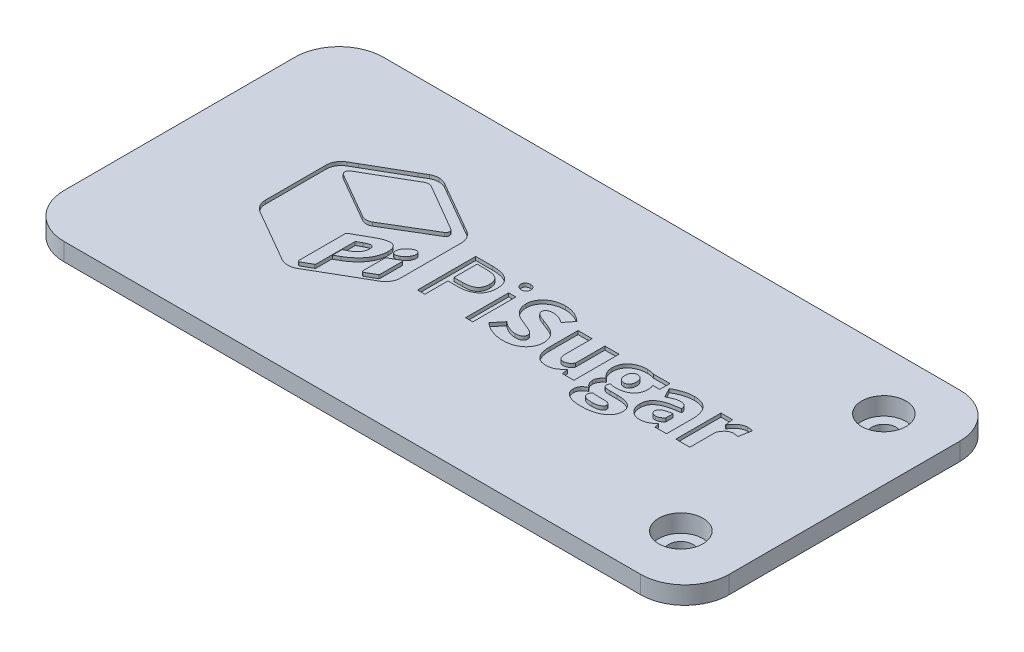
SolidWorks part; units mm, degrees
ref_plane "前视基准面" through (0, 0, 0) normal (0, 0, 1) x (1, 0, 0)
ref_plane "上视基准面" through (0, 0, 0) normal (0, 1, 0) x (1, 0, 0)
ref_plane "右视基准面" through (0, 0, 0) normal (1, 0, 0) x (0, 0, -1)
sketch "zero" plane through (0, 0, 0) normal (0, 1, 0) x (1, 0, 0)
  line L1 (-29.5, 15) -> (29.5, 15)
  line L2 (-32.5, 12) -> (-32.5, -12)
  line L3 (-29.5, -15) -> (29.5, -15)
  line L4 (32.5, 12) -> (32.5, -12)
  line L5 (-32.5, 15) -> (32.5, -15) construction
  line L6 (-32.5, -15) -> (32.5, 15) construction
  line L7 (-25.7, -15) -> (-14.5, -15)
  line L8 (-25.7, -15) -> (-25.7, -9.6569)
  line L9 (-25.7, -9.6569) -> (-14.5, -9.6569)
  line L10 (-14.5, -15) -> (-14.5, -9.6569)
  line L11 (5.2, -15) -> (12.7, -15)
  line L12 (5.2, -15) -> (5.2, -11)
  line L13 (5.2, -11) -> (12.7, -11)
  line L14 (12.7, -15) -> (12.7, -11)
  line L15 (17.8, -15) -> (25.3, -15)
  line L16 (17.8, -15) -> (17.8, -11)
  line L17 (17.8, -11) -> (25.3, -11)
  line L18 (25.3, -15) -> (25.3, -11)
  line L19 (-32.5, 7.7) -> (-19.5, 7.7)
  line L20 (-32.5, 7.7) -> (-32.5, -4.3)
  line L21 (-32.5, -4.3) -> (-19.5, -4.3)
  line L22 (-19.5, 7.7) -> (-19.5, -4.3)
  line L23 (-25.5, 14) -> (25.5, 14)
  line L24 (-25.5, 14) -> (-25.5, 8.8)
  line L25 (-25.5, 8.8) -> (25.5, 8.8)
  line L26 (25.5, 14) -> (25.5, 8.8)
  line L27 (-19.5, 7.2329) -> (-35.5, 7.2329)
  line L28 (-19.5, 7.2329) -> (-19.5, -3.7671)
  line L29 (-19.5, -3.7671) -> (-35.5, -3.7671)
  line L30 (-35.5, 7.2329) -> (-35.5, -3.7671)
  arc A0 (29.5, -15) -> (32.5, -12) centre (29.5, -12) ccw
  arc A1 (29.5, 15) -> (32.5, 12) centre (29.5, 12) cw
  arc A2 (-32.5, -12) -> (-29.5, -15) centre (-29.5, -12) ccw
  arc A3 (-29.5, 15) -> (-32.5, 12) centre (-29.5, 12) ccw
  circle A4 centre (-29, 11.4) radius 3
  circle A5 centre (-29, -11.5) radius 3
  circle A6 centre (29, 11.4) radius 3
  circle A7 centre (29, -11.5) radius 3
  circle A8 centre (-29, 11.4) radius 1.375
  circle A9 centre (-29, -11.5) radius 1.375
  circle A10 centre (29, -11.5) radius 1.375
  circle A11 centre (29, 11.4) radius 1.375
  point P0 (0, 0)
  dimension "D3" = 3
  dimension "D4" = 6
  dimension "D9" = 2.75
  dimension "D1" = 65
  dimension "D2" = 30
  dimension "D5" = 3.6
  dimension "D6" = 3.5
  dimension "D7" = 3.5
  dimension "D8" = 3.5
  dimension "D10" = 12
  dimension "D11" = 7.3
  dimension "D12" = 13
  dimension "D13" = 11.2
  dimension "D14" = 6.8
  dimension "D15" = 19.7
  dimension "D16" = 7.5
  dimension "D17" = 7.5
  dimension "D18" = 5.1
  dimension "D19" = 4
  dimension "D20" = 5.2
  dimension "D21" = 7
  dimension "D22" = 7
  dimension "D23" = 1
  dimension "D24" = 11
  dimension "D25" = 16
sketch "sugar" plane through (0, 0, 0) normal (0, 1, 0) x (1, 0, 0)
  line L1 (-29.5, 15) -> (29.5, 15)
  line L2 (-32.5, 12) -> (-32.5, -12)
  line L3 (-29.5, -15) -> (29.5, -15)
  line L4 (32.5, 12) -> (32.5, -12)
  line L5 (-32.5, 15) -> (32.5, -15) construction
  line L6 (-32.5, -15) -> (32.5, 15) construction
  line L7 (23.5, -11.5) -> (19.5, -11.5)
  line L8 (23.5, -11.5) -> (23.5, -13.9082)
  line L9 (23.5, -13.9082) -> (19.5, -13.9082)
  line L10 (19.5, -11.5) -> (19.5, -13.9082)
  line L11 (16, -11.0071) -> (8.5, -11.0071)
  line L12 (16, -11.0071) -> (16, -15)
  line L13 (16, -15) -> (8.5, -15)
  line L14 (8.5, -11.0071) -> (8.5, -15)
  line L15 (20.5, -13.9082) -> (22.5, -13.9082)
  line L16 (20.5, -13.9082) -> (20.5, -14.8173)
  line L17 (20.5, -14.8173) -> (22.5, -14.8173)
  line L18 (22.5, -13.9082) -> (22.5, -14.8173)
  arc A0 (29.5, 15) -> (32.5, 12) centre (29.5, 12) cw
  arc A1 (29.5, -15) -> (32.5, -12) centre (29.5, -12) ccw
  arc A2 (-32.5, -12) -> (-29.5, -15) centre (-29.5, -12) ccw
  arc A3 (-29.5, 15) -> (-32.5, 12) centre (-29.5, 12) ccw
  circle A4 centre (-29, 11.4) radius 3
  circle A5 centre (-29, 11.4) radius 1.375
  circle A6 centre (-29, -11.5) radius 3
  circle A7 centre (-29, -11.5) radius 1.375
  circle A8 centre (29, 11.4) radius 3
  circle A9 centre (29, 11.4) radius 1.375
  circle A10 centre (29, -11.5) radius 3
  circle A11 centre (29, -11.5) radius 1.375
  dimension "D3" = 3
  dimension "D1" = 65
  dimension "D2" = 30
  dimension "D4" = 9
  dimension "D5" = 4
  dimension "D6" = 3.5
  dimension "D7" = 7.5
  dimension "D8" = 2
  dimension "D9" = 1
sketch "case" plane through (0, 0, 0) normal (0, 1, 0) x (1, 0, 0)
  line L1 (-34.0422, 18) -> (30.9578, 18)
  line L2 (-39.0422, 13) -> (-39.0422, -13)
  line L3 (-34.0422, -18) -> (30.9578, -18)
  line L4 (35.9578, 13) -> (35.9578, -13)
  line L5 (-39.0422, 18) -> (35.9578, -18) construction
  line L6 (-39.0422, -18) -> (35.9578, 18) construction
  arc A0 (-39.0422, -13) -> (-34.0422, -18) centre (-34.0422, -13) ccw
  arc A1 (30.9578, -18) -> (35.9578, -13) centre (30.9578, -13) ccw
  arc A2 (30.9578, 18) -> (35.9578, 13) centre (30.9578, 13) cw
  arc A3 (-34.0422, 18) -> (-39.0422, 13) centre (-34.0422, 13) ccw
  point P0 (-1.5422, 0)
  point P3 (-1.5422, 0)
  dimension "D3" = 5
  dimension "D1" = 75
  dimension "D2" = 36
extrude "凸台-拉伸2" add sketch "case" along normal blind 2
sketch "草图2" plane through (0, 0, 0) normal (0, 1, 0) x (1, 0, 0)
  line L4 (-34.0422, -14.7) -> (30.9578, -14.7)
  line L5 (32.6578, -13) -> (32.6578, 13)
  line L6 (30.9578, 14.7) -> (-34.0422, 14.7)
  line L7 (-35.7422, 13) -> (-35.7422, -13)
  line L8 (33.8578, -13) -> (33.8578, 13)
  line L9 (30.9578, 15.9) -> (-34.0422, 15.9)
  line L10 (-36.9422, 13) -> (-36.9422, -13)
  line L11 (-34.0422, -15.9) -> (30.9578, -15.9)
  line L12 (33.8578, -13) -> (33.8578, 13)
  line L13 (30.9578, 15.9) -> (-34.0422, 15.9)
  line L14 (-36.9422, 13) -> (-36.9422, -13)
  line L15 (-34.0422, -15.9) -> (30.9578, -15.9)
  arc A4 (30.9578, -14.7) -> (32.6578, -13) centre (30.9578, -13) ccw
  arc A5 (32.6578, 13) -> (30.9578, 14.7) centre (30.9578, 13) ccw
  arc A6 (-34.0422, 14.7) -> (-35.7422, 13) centre (-34.0422, 13) ccw
  arc A7 (-35.7422, -13) -> (-34.0422, -14.7) centre (-34.0422, -13) ccw
  arc A8 (30.9578, -15.9) -> (33.8578, -13) centre (30.9578, -13) ccw
  arc A9 (33.8578, 13) -> (30.9578, 15.9) centre (30.9578, 13) ccw
  arc A10 (-34.0422, 15.9) -> (-36.9422, 13) centre (-34.0422, 13) ccw
  arc A11 (-36.9422, -13) -> (-34.0422, -15.9) centre (-34.0422, -13) ccw
  arc A12 (30.9578, -15.9) -> (33.8578, -13) centre (30.9578, -13) ccw
  arc A13 (33.8578, 13) -> (30.9578, 15.9) centre (30.9578, 13) ccw
  arc A14 (-34.0422, 15.9) -> (-36.9422, 13) centre (-34.0422, 13) ccw
  arc A15 (-36.9422, -13) -> (-34.0422, -15.9) centre (-34.0422, -13) ccw
  dimension "D1" = 2.1
  dimension "D2" = 1.2
extrude "凸台-拉伸3" add sketch "草图2" against normal blind 1
sketch "草图4" plane through (0, 0, 0) normal (0, 1, 0) x (1, 0, 0)
  line L1 (-35.7422, -5) -> (-31.7422, -5)
  line L2 (-35.7422, -5) -> (-35.7422, 5)
  line L3 (-35.7422, 5) -> (-31.7422, 5)
  line L4 (-31.7422, -5) -> (-31.7422, 5)
  line L5 (-35.7422, -5) -> (-31.7422, 5) construction
  line L6 (-35.7422, 5) -> (-31.7422, -5) construction
  line L7 (-35.7422, 13) -> (-35.7422, -13) construction
  point P0 (-33.7422, 0)
  dimension "D1" = 4
  dimension "D2" = 10
  dimension "D3" = 0
ref_plane "基准面1" through (33.8578, 0, 0) normal (1, 0, 0) x (0, 0, -1)
extrude "凸台-拉伸7" add sketch "草图4" against normal blind 2.2
ref_plane "基准面2" through (-36.9422, 0, 0) normal (-1, 0, 0) x (0, 0, 1)
ref_plane "基准面3" through (0, 2, 0) normal (0, 1, 0) x (1, 0, 0)
sketch "草图7" plane through (0, 2, 0) normal (0, 1, 0) x (1, 0, 0)
  line L0 (30.9578, 18) -> (-34.0422, 18) construction
  line L1 (-34.0422, -18) -> (30.9578, -18) construction
  line L2 (35.9578, -13) -> (35.9578, 13) construction
  circle A0 centre (28.9978, 11.4) radius 1.375
  circle A1 centre (28.9978, -11.5) radius 1.375
  dimension "D1" = 2.75
  dimension "D2" = 6.6
  dimension "D3" = 6.5
  dimension "D4" = 6.96
sketch "草图9" plane through (0, 2, 0) normal (0, 1, 0) x (1, 0, 0)
  circle A0 centre (28.9978, 11.4) radius 2.5
  circle A1 centre (28.9978, -11.5) radius 2.5
  dimension "D1" = 5
sketch "草图10" plane through (0, 2, 0) normal (0, 1, 0) x (1, 0, 0)
  circle A0 centre (28.9978, 11.4) radius 3.5
  circle A1 centre (28.9978, -11.5) radius 3.5
  dimension "D1" = 7
extrude "凸台-拉伸10" add sketch "草图10" against normal blind 3
extrude "切除-拉伸3" cut sketch "草图9" against normal blind 2
extrude "切除-拉伸4" cut sketch "草图7" against normal blind 4
ref_plane "基准面4" through (-31.7422, 0, 0) normal (1, 0, 0) x (0, 0, -1)
sketch "草图12" plane through (-31.7422, 0, 0) normal (1, 0, 0) x (0, 0, -1)
  line L1 (-5, -2.2) -> (5, -2.2)
  line L2 (-5, -2.2) -> (-5, -1)
  line L3 (-5, -1) -> (5, -1)
  line L4 (5, -2.2) -> (5, -1)
extrude "凸台-拉伸11" add sketch "草图12" against normal blind 6.7
chamfer "倒角5" distance 1 angle 45 1 edges at (-38.4422, -1, 0)
chamfer "倒角6" distance 1 angle 45 3 edges at (-33.7422, 0, -5) (-31.7422, 0, 0) (-33.7422, 0, 5)
chamfer "倒角8" distance 1 angle 45 1 edges at (-31.7422, -2.2, 0)
sketch "草图14" plane through (0, 2, 0) normal (0, 1, 0) x (1, 0, 0)
  line L0 (-12.3681, 5.7189) -> (-13.1887, 6.1919)
  line L1 (-13.1887, 6.1919) -> (-17.4456, 8.648)
  line L2 (-17.4456, 8.648) -> (-18.2661, 9.1267)
  line L3 (-19.9872, 9.1267) -> (-20.8078, 8.648)
  line L4 (-20.8078, 8.648) -> (-25.0647, 6.1919)
  line L5 (-25.0647, 6.1919) -> (-25.8853, 5.7189)
  line L6 (-26.7458, 4.2316) -> (-26.7458, -2.584)
  line L7 (-25.8853, -4.0714) -> (-25.0647, -4.5444)
  line L8 (-25.0647, -4.5444) -> (-20.8078, -7.0005)
  line L9 (-20.8078, -7.0005) -> (-19.9872, -7.4792)
  line L10 (-18.2661, -7.4792) -> (-17.4456, -7.0005)
  line L11 (-17.4456, -7.0005) -> (-13.1887, -4.5444)
  line L12 (-13.1887, -4.5444) -> (-12.3681, -4.0714)
  line L13 (-11.5076, -2.584) -> (-11.5076, 4.2316)
  line L14 (-24.7911, 5.0408) -> (-19.5256, 8.0839)
  line L15 (-18.7221, 8.0839) -> (-13.485, 5.0351)
  line L16 (-13.4793, 4.3341) -> (-18.5682, 1.2911)
  line L17 (-16.9897, -3.8662) -> (-17.5823, -4.1967)
  line L18 (-17.6394, -4.2936) -> (-17.6394, -6.0032)
  line L19 (-17.6963, -6.1001) -> (-18.8019, -6.7269)
  line L20 (-18.9671, -6.6301) -> (-18.9671, -1.3531)
  line L21 (-18.9102, -1.2562) -> (-17.0296, -0.1906)
  line L22 (-13.0862, -3.5129) -> (-14.1803, -4.134)
  line L23 (-14.3455, -4.0372) -> (-14.3455, -1.5241)
  line L24 (-14.2885, -1.4272) -> (-13.1944, -0.8117)
  line L25 (-13.0291, -0.9086) -> (-13.0291, -3.416)
  line L26 (-17.0581, -2.8519) -> (-17.5823, -3.114)
  line L27 (-17.6394, -2.9943) -> (-17.6394, -1.6494)
  line L28 (-17.5823, -1.5526) -> (-17.0923, -1.279)
  line L29 (-7.5129, 3.7529) -> (-9.3877, 3.7529)
  line L30 (-9.3877, 3.7529) -> (-9.3877, -2.812)
  line L31 (-9.3877, -2.812) -> (-8.5557, -2.812)
  line L32 (-8.5557, -2.812) -> (-8.5557, -0.2077)
  line L33 (-8.5557, -0.2077) -> (-7.4672, -0.2077)
  line L34 (-7.5755, 0.4648) -> (-8.5557, 0.4648)
  line L35 (-8.5557, 0.4648) -> (-8.5557, 3.0804)
  line L36 (-8.5557, 3.0804) -> (-7.6097, 3.0804)
  line L37 (-3.974, 2.0547) -> (-3.974, -2.812)
  line L38 (-3.974, -2.812) -> (-3.159, -2.812)
  line L39 (-3.159, -2.812) -> (-3.159, 2.0547)
  line L40 (-3.159, 2.0547) -> (-3.974, 2.0547)
  line L41 (1.548, 0.9776) -> (0.716, 1.3082)
  line L42 (1.8728, 2.0946) -> (2.6707, 3.0975)
  line L43 (-0.5605, 0.1342) -> (0.2886, -0.2248)
  line L44 (-1.2614, -0.8744) -> (-2.1674, -1.98)
  line L45 (6.6541, 2.2826) -> (6.6541, -1.0568)
  line L46 (5.2123, -0.6693) -> (5.2123, 2.2826)
  line L47 (5.2123, 2.2826) -> (3.6223, 2.2826)
  line L48 (3.6223, 2.2826) -> (3.6223, -0.8687)
  line L49 (6.8022, -2.111) -> (6.8364, -2.111)
  line L50 (6.8364, -2.111) -> (6.9504, -2.812)
  line L51 (6.9504, -2.812) -> (8.2496, -2.812)
  line L52 (8.2496, -2.812) -> (8.2496, 2.2826)
  line L53 (8.2496, 2.2826) -> (6.6541, 2.2826)
  line L54 (12.1019, -1.809) -> (11.2984, -1.809)
  line L55 (13.1961, 1.1315) -> (13.9825, 1.1315)
  line L56 (13.9825, 1.1315) -> (13.9825, 2.2826)
  line L57 (13.9825, 2.2826) -> (12.1134, 2.2826)
  line L58 (9.8623, -0.7605) -> (9.8623, -0.7946)
  line L59 (9.7655, -2.6239) -> (9.7655, -2.6695)
  line L60 (11.3155, -3.0285) -> (11.8, -3.0285)
  line L61 (14.4384, 1.7413) -> (14.9968, 0.6927)
  line L62 (17.2421, -2.2991) -> (17.282, -2.2991)
  line L63 (17.282, -2.2991) -> (17.3959, -2.812)
  line L64 (17.3959, -2.812) -> (18.6953, -2.812)
  line L65 (18.6953, -2.812) -> (18.6953, 0.0829)
  line L66 (17.0997, -0.4812) -> (17.0997, -1.2961)
  line L67 (21.1856, 1.3994) -> (21.1514, 1.3994)
  line L68 (21.1514, 1.3994) -> (21.0432, 2.2826)
  line L69 (21.0432, 2.2826) -> (19.7439, 2.2826)
  line L70 (19.7439, 2.2826) -> (19.7439, -2.812)
  line L71 (19.7439, -2.812) -> (21.3281, -2.812)
  line L72 (21.3281, -2.812) -> (21.3281, 0.1)
  line L73 (22.9864, 0.9321) -> (23.2542, 2.3054)
  line L74 (-17.5823, -3.114) -> (-17.5823, -4.1967)
  line L75 (-17.6394, -2.9943) -> (-17.6394, -4.2936)
  spline S0 degree 3 poles (-18.2661, 9.1267) (-18.534, 9.2749) (-18.8303, 9.3547) (-19.1266, 9.3547) knots 3 3 3 3 4 4 4 4
  spline S1 degree 3 poles (-19.1266, 9.3547) (-19.423, 9.3547) (-19.7193, 9.2749) (-19.9872, 9.1267) knots 4 4 4 4 5 5 5 5
  spline S2 degree 3 poles (-25.8853, 5.7189) (-26.4153, 5.4112) (-26.7458, 4.8413) (-26.7458, 4.2316) knots 8 8 8 8 9 9 9 9
  spline S3 degree 3 poles (-26.7458, -2.584) (-26.7458, -3.1995) (-26.4153, -3.7637) (-25.8853, -4.0714) knots 10 10 10 10 11 11 11 11
  spline S4 degree 3 poles (-19.9872, -7.4792) (-19.7193, -7.633) (-19.423, -7.7071) (-19.1266, -7.7071) knots 14 14 14 14 15 15 15 15
  spline S5 degree 3 poles (-19.1266, -7.7071) (-18.8303, -7.7071) (-18.534, -7.633) (-18.2661, -7.4792) knots 15 15 15 15 16 16 16 16
  spline S6 degree 3 poles (-12.3681, -4.0714) (-11.8324, -3.7637) (-11.5076, -3.1995) (-11.5076, -2.584) knots 19 19 19 19 20 20 20 20
  spline S7 degree 3 poles (-11.5076, 4.2316) (-11.5076, 4.8413) (-11.8324, 5.4112) (-12.3681, 5.7189) knots 21 21 21 21 22 22 22 22
  spline S8 degree 2 poles (-19.6795, 1.2911) (-24.831, 4.2658) (-24.8424, 4.2715) knots 0 0 0 1 1 1
  spline S9 degree 3 poles (-24.8424, 4.2715) (-25.1102, 4.4652) (-25.0818, 4.8755) (-24.7911, 5.0408) knots 1 1 1 1 2 2 2 2
  spline S10 degree 3 poles (-19.5256, 8.0839) (-19.2805, 8.2263) (-18.9728, 8.2263) (-18.7221, 8.0839) knots 3 3 3 3 4 4 4 4
  spline S11 degree 3 poles (-13.485, 5.0351) (-13.2172, 4.8812) (-13.2115, 4.4937) (-13.4793, 4.3341) knots 5 5 5 5 6 6 6 6
  spline S12 degree 3 poles (-18.5682, 1.2911) (-18.9102, 1.0916) (-19.3376, 1.0916) (-19.6795, 1.2911) knots 7 7 7 7 8 8 8 8
  spline S14 degree 3 poles (-17.6394, -6.0032) (-17.6394, -6.0431) (-17.6564, -6.0773) (-17.6963, -6.1001) knots 3 3 3 3 4 4 4 4
  spline S15 degree 3 poles (-18.8019, -6.7269) (-18.8759, -6.7668) (-18.9671, -6.7156) (-18.9671, -6.6301) knots 5 5 5 5 6 6 6 6
  spline S16 degree 3 poles (-18.9671, -1.3531) (-18.9671, -1.3132) (-18.95, -1.2733) (-18.9102, -1.2562) knots 7 7 7 7 8 8 8 8
  spline S17 degree 3 poles (-17.0296, -0.1906) (-15.8101, 0.499) (-14.8015, 0.6357) (-14.8015, -0.732) knots 9 9 9 9 10 10 10 10
  spline S18 degree 3 poles (-14.8015, -0.732) (-14.8015, -2.0484) (-15.8215, -3.2052) (-16.9897, -3.8662) knots 10 10 10 10 11 11 11 11
  spline S19 degree 3 poles (-13.0291, -3.416) (-13.0291, -3.4559) (-13.0519, -3.4958) (-13.0862, -3.5129) knots 0 0 0 0 1 1 1 1
  spline S20 degree 3 poles (-14.1803, -4.134) (-14.2543, -4.1739) (-14.3455, -4.1226) (-14.3455, -4.0372) knots 2 2 2 2 3 3 3 3
  spline S21 degree 3 poles (-14.3455, -1.5241) (-14.3455, -1.4842) (-14.3227, -1.45) (-14.2885, -1.4272) knots 4 4 4 4 5 5 5 5
  spline S22 degree 3 poles (-13.1944, -0.8117) (-13.1203, -0.7719) (-13.0291, -0.8231) (-13.0291, -0.9086) knots 6 6 6 6 7 7 7 7
  spline S23 degree 3 poles (-13.6845, 0.858) (-13.2457, 1.1087) (-12.9323, 1.0004) (-12.9323, 0.6015) (-12.9323, 0.2083) (-13.2457, -0.2533) (-13.6845, -0.4983) knots 2 2 2 2 3 3 3 4 4 4 4
  spline S24 degree 3 poles (-13.6845, -0.4983) (-14.1289, -0.7547) (-14.4424, -0.6465) (-14.4424, -0.2533) (-14.4424, 0.1514) (-14.1289, 0.6072) (-13.6845, 0.858) knots 0 0 0 0 1 1 1 2 2 2 2
  spline S25 degree 3 poles (-16.1007, -1.4671) (-16.1007, -2.0085) (-16.4084, -2.4871) (-17.0581, -2.8519) knots 0 0 0 0 1 1 1 1
  spline S27 degree 3 poles (-17.6394, -1.6494) (-17.6394, -1.6095) (-17.6166, -1.5697) (-17.5823, -1.5526) knots 4 4 4 4 5 5 5 5
  spline S28 degree 3 poles (-17.0923, -1.279) (-16.454, -0.9143) (-16.1007, -0.9086) (-16.1007, -1.4671) knots 6 6 6 6 7 7 7 7
  spline S29 degree 3 poles (-7.4672, -0.2077) (-6.0369, -0.2077) (-5.051, 0.442) (-5.051, 1.8268) knots 5 5 5 5 6 6 6 6
  spline S30 degree 3 poles (-5.051, 1.8268) (-5.051, 3.2628) (-6.0369, 3.7529) (-7.5129, 3.7529) knots 6 6 6 6 7 7 7 7
  spline S31 degree 3 poles (-7.6097, 3.0804) (-6.4585, 3.0804) (-5.8773, 2.7784) (-5.8773, 1.8268) knots 3 3 3 3 4 4 4 4
  spline S32 degree 3 poles (-5.8773, 1.8268) (-5.8773, 0.8865) (-6.4187, 0.4648) (-7.5755, 0.4648) knots 4 4 4 4 5 5 5 5
  spline S33 degree 3 poles (-3.5637, 3.0577) (-3.2389, 3.0577) (-2.9995, 3.2799) (-2.9995, 3.5819) (-2.9995, 3.9182) (-3.2389, 4.1119) (-3.5637, 4.1119) knots 2 2 2 2 3 3 3 4 4 4 4
  spline S34 degree 3 poles (-3.5637, 4.1119) (-3.8884, 4.1119) (-4.1278, 3.9182) (-4.1278, 3.5819) (-4.1278, 3.2799) (-3.8884, 3.0577) (-3.5637, 3.0577) knots 0 0 0 0 1 1 1 2 2 2 2
  spline S35 degree 3 poles (0.716, 1.3082) (0.1291, 1.5418) (-0.2926, 1.6843) (-0.2926, 2.0547) knots 1 1 1 1 2 2 2 2
  spline S36 degree 3 poles (-0.2926, 2.0547) (-0.2926, 2.408) (0.0094, 2.6075) (0.5052, 2.6075) knots 2 2 2 2 3 3 3 3
  spline S37 degree 3 poles (0.5052, 2.6075) (1.0237, 2.6075) (1.4341, 2.4308) (1.8728, 2.0946) knots 3 3 3 3 4 4 4 4
  spline S38 degree 3 poles (2.6707, 3.0975) (2.0894, 3.6845) (1.2745, 3.9808) (0.5052, 3.9808) knots 5 5 5 5 6 6 6 6
  spline S39 degree 3 poles (0.5052, 3.9808) (-0.9138, 3.9808) (-1.9167, 3.0804) (-1.9167, 1.9635) knots 6 6 6 6 7 7 7 7
  spline S40 degree 3 poles (-1.9167, 1.9635) (-1.9167, 0.9947) (-1.2614, 0.4135) (-0.5605, 0.1342) knots 7 7 7 7 8 8 8 8
  spline S41 degree 3 poles (0.2886, -0.2248) (0.8585, -0.4641) (1.2289, -0.5895) (1.2289, -0.977) knots 9 9 9 9 10 10 10 10
  spline S42 degree 3 poles (1.2289, -0.977) (1.2289, -1.336) (0.9497, -1.5582) (0.357, -1.5582) knots 10 10 10 10 11 11 11 11
  spline S43 degree 3 poles (0.357, -1.5582) (-0.1672, -1.5582) (-0.7884, -1.279) (-1.2614, -0.8744) knots 11 11 11 11 12 12 12 12
  spline S44 degree 3 poles (-2.1674, -1.98) (-1.4779, -2.6125) (-0.5434, -2.9373) (0.3228, -2.9373) knots 13 13 13 13 14 14 14 14
  spline S45 degree 3 poles (0.3228, -2.9373) (1.9356, -2.9373) (2.8701, -1.9629) (2.8701, -0.8516) knots 14 14 14 14 15 15 15 15
  spline S46 degree 3 poles (2.8701, -0.8516) (2.8701, 0.0886) (2.3744, 0.6471) (1.548, 0.9776) knots 15 15 15 15 16 16 16 16
  spline S47 degree 3 poles (6.6541, -1.0568) (6.3862, -1.4329) (6.1639, -1.5754) (5.805, -1.5754) knots 1 1 1 1 2 2 2 2
  spline S48 degree 3 poles (5.805, -1.5754) (5.4003, -1.5754) (5.2123, -1.3759) (5.2123, -0.6693) knots 2 2 2 2 3 3 3 3
  spline S49 degree 3 poles (3.6223, -0.8687) (3.6223, -2.1395) (4.0954, -2.9373) (5.2066, -2.9373) knots 6 6 6 6 7 7 7 7
  spline S50 degree 3 poles (5.2066, -2.9373) (5.9018, -2.9373) (6.3805, -2.6125) (6.8022, -2.111) knots 7 7 7 7 8 8 8 8
  spline S51 degree 3 poles (11.2984, -1.809) (10.7514, -1.809) (10.5462, -1.7007) (10.5462, -1.4671) knots 1 1 1 1 2 2 2 2
  spline S52 degree 3 poles (10.5462, -1.4671) (10.5462, -1.2961) (10.5861, -1.2163) (10.7057, -1.1081) knots 2 2 2 2 3 3 3 3
  spline S53 degree 3 poles (10.7057, -1.1081) (10.9281, -1.1707) (11.1331, -1.1993) (11.3041, -1.1993) knots 3 3 3 3 4 4 4 4
  spline S54 degree 3 poles (11.3041, -1.1993) (12.4324, -1.1993) (13.3386, -0.6807) (13.3386, 0.5103) knots 4 4 4 4 5 5 5 5
  spline S55 degree 3 poles (13.3386, 0.5103) (13.3386, 0.7554) (13.2758, 0.989) (13.1961, 1.1315) knots 5 5 5 5 6 6 6 6
  spline S56 degree 3 poles (12.1134, 2.2826) (11.8797, 2.3681) (11.6005, 2.408) (11.3041, 2.408) knots 9 9 9 9 10 10 10 10
  spline S57 degree 3 poles (11.3041, 2.408) (10.2043, 2.408) (9.1728, 1.8039) (9.1728, 0.5559) knots 10 10 10 10 11 11 11 11
  spline S58 degree 3 poles (9.1728, 0.5559) (9.1728, -0.0367) (9.5034, -0.5097) (9.8623, -0.7605) knots 11 11 11 11 12 12 12 12
  spline S59 degree 3 poles (9.8623, -0.7946) (9.5318, -1.0283) (9.2982, -1.3873) (9.2982, -1.7463) knots 13 13 13 13 14 14 14 14
  spline S60 degree 3 poles (9.2982, -1.7463) (9.2982, -2.1737) (9.4977, -2.4416) (9.7655, -2.6239) knots 14 14 14 14 15 15 15 15
  spline S61 degree 3 poles (9.7655, -2.6695) (9.2925, -2.9089) (9.0418, -3.2508) (9.0418, -3.6725) knots 16 16 16 16 17 17 17 17
  spline S62 degree 3 poles (9.0418, -3.6725) (9.0418, -4.5842) (10.0048, -4.9547) (11.1788, -4.9547) knots 17 17 17 17 18 18 18 18
  spline S63 degree 3 poles (11.1788, -4.9547) (12.951, -4.9547) (14.0623, -4.1911) (14.0623, -3.114) knots 18 18 18 18 19 19 19 19
  spline S64 degree 3 poles (14.0623, -3.114) (14.0623, -2.1908) (13.3557, -1.809) (12.1019, -1.809) knots 19 19 19 19 20 20 20 20
  spline S65 degree 3 poles (11.3041, -0.2419) (10.9395, -0.2419) (10.6602, 0.026) (10.6602, 0.5559) (10.6602, 1.0745) (10.9395, 1.3424) (11.3041, 1.3424) knots 2 2 2 2 3 3 3 4 4 4 4
  spline S66 degree 3 poles (11.3041, 1.3424) (11.6802, 1.3424) (11.9481, 1.0745) (11.9481, 0.5559) (11.9481, 0.026) (11.6802, -0.2419) (11.3041, -0.2419) knots 0 0 0 0 1 1 1 2 2 2 2
  spline S67 degree 3 poles (11.4295, -3.9574) (10.7742, -3.9574) (10.3468, -3.7807) (10.3468, -3.4217) knots 0 0 0 0 1 1 1 1
  spline S68 degree 3 poles (10.3468, -3.4217) (10.3468, -3.2508) (10.4265, -3.1083) (10.5861, -2.9658) knots 1 1 1 1 2 2 2 2
  spline S69 degree 3 poles (10.5861, -2.9658) (10.7514, -3.0114) (10.9452, -3.0285) (11.3155, -3.0285) knots 2 2 2 2 3 3 3 3
  spline S70 degree 3 poles (11.8, -3.0285) (12.2729, -3.0285) (12.5408, -3.0912) (12.5408, -3.3932) knots 4 4 4 4 5 5 5 5
  spline S71 degree 3 poles (12.5408, -3.3932) (12.5408, -3.7181) (12.0849, -3.9574) (11.4295, -3.9574) knots 5 5 5 5 6 6 6 6
  spline S72 degree 3 poles (16.6324, 2.408) (15.8402, 2.408) (15.1109, 2.1402) (14.4384, 1.7413) knots 0 0 0 0 1 1 1 1
  spline S73 degree 3 poles (14.9968, 0.6927) (15.5041, 0.9776) (15.9258, 1.1372) (16.3304, 1.1372) knots 2 2 2 2 3 3 3 3
  spline S74 degree 3 poles (16.3304, 1.1372) (16.8489, 1.1372) (17.0655, 0.8979) (17.0997, 0.4876) knots 3 3 3 3 4 4 4 4
  spline S75 degree 3 poles (17.0997, 0.4876) (15.1109, 0.271) (14.2674, -0.3102) (14.2674, -1.3873) knots 4 4 4 4 5 5 5 5
  spline S76 degree 3 poles (14.2674, -1.3873) (14.2674, -2.2364) (14.843, -2.9373) (15.7833, -2.9373) knots 5 5 5 5 6 6 6 6
  spline S77 degree 3 poles (15.7833, -2.9373) (16.3475, -2.9373) (16.8204, -2.6752) (17.2421, -2.2991) knots 6 6 6 6 7 7 7 7
  spline S78 degree 3 poles (18.6953, 0.0829) (18.6953, 1.6786) (17.9488, 2.408) (16.6324, 2.408) knots 11 11 11 11 12 12 12 12
  spline S79 degree 3 poles (17.0997, -1.2961) (16.866, -1.5469) (16.6552, -1.7007) (16.3304, -1.7007) knots 0 0 0 0 1 1 1 1
  spline S80 degree 3 poles (16.3304, -1.7007) (15.9998, -1.7007) (15.7833, -1.5582) (15.7833, -1.2619) knots 1 1 1 1 2 2 2 2
  spline S81 degree 3 poles (15.7833, -1.2619) (15.7833, -0.9029) (16.1081, -0.618) (17.0997, -0.4812) knots 2 2 2 2 3 3 3 3
  spline S82 degree 3 poles (22.6388, 2.408) (22.1259, 2.408) (21.5617, 2.0775) (21.1856, 1.3994) knots 0 0 0 0 1 1 1 1
  spline S83 degree 3 poles (21.3281, 0.1) (21.5959, 0.7725) (22.0518, 1.0118) (22.4279, 1.0118) knots 7 7 7 7 8 8 8 8
  spline S84 degree 3 poles (22.4279, 1.0118) (22.6559, 1.0118) (22.804, 0.9776) (22.9864, 0.9321) knots 8 8 8 8 9 9 9 9
  spline S85 degree 3 poles (23.2542, 2.3054) (23.1117, 2.3681) (22.9408, 2.408) (22.6388, 2.408) knots 10 10 10 10 11 11 11 11
extrude "切除-拉伸8" cut sketch "草图14" against normal blind 0.4
